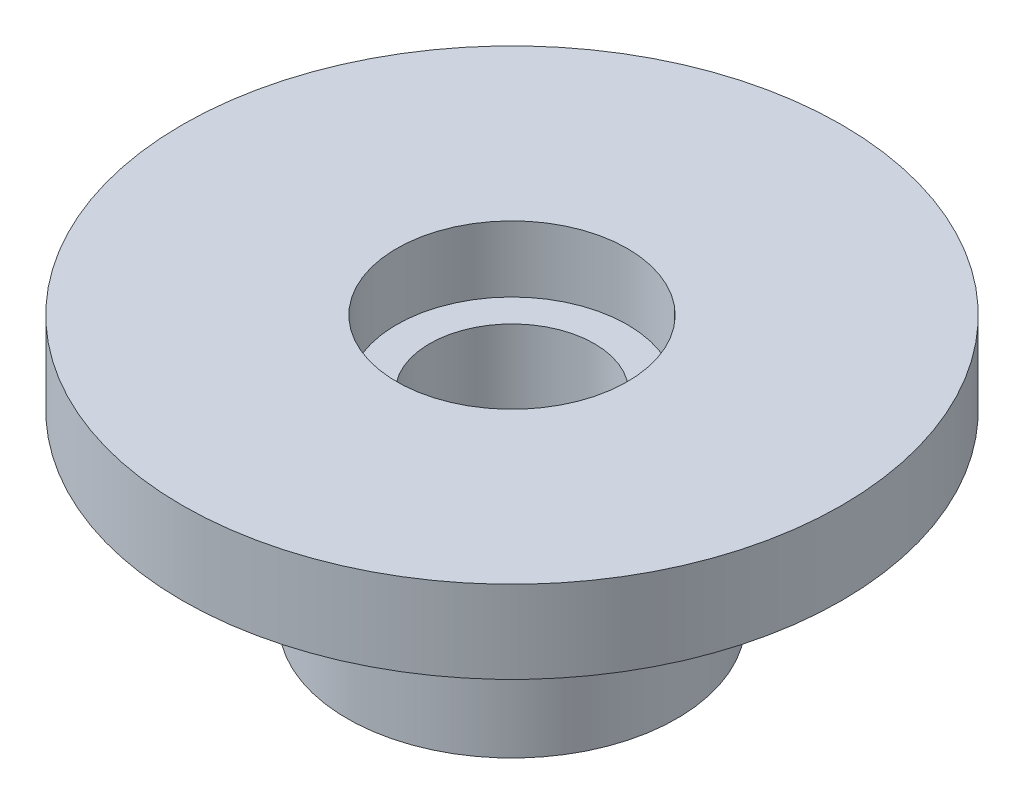
SolidWorks part; units mm, degrees
ref_plane "Front Plane" through (0, 0, 0) normal (0, 0, 1) x (1, 0, 0)
ref_plane "Top Plane" through (0, 0, 0) normal (0, 1, 0) x (1, 0, 0)
ref_plane "Right Plane" through (0, 0, 0) normal (1, 0, 0) x (0, 0, -1)
sketch "Sketch1" plane through (0, 0, 0) normal (0, 0, 1) x (1, 0, 0)
  line L0 (0, 0) -> (0, 19.3754) construction
  line L2 (2.5, 6.1) -> (3.5, 6.1)
  line L3 (3.5, 6.1) -> (3.5, 8.1)
  line L4 (3.5, 8.1) -> (10, 8.1)
  line L5 (10, 8.1) -> (10, 5.6)
  line L6 (10, 5.6) -> (5, 5.6)
  line L7 (5, 5.6) -> (5, 0)
  line L8 (5, 0) -> (2.5, 0)
  line L9 (2.5, 6.1) -> (2.5, 0)
  dimension "D1" = 20
  dimension "D2" = 7
  dimension "D3" = 10
  dimension "D4" = 5
  dimension "D5" = 2.5
  dimension "D6" = 5.6
  dimension "D7" = 2
revolve "Revolve1" add sketch "Sketch1" angle 360 about L0
